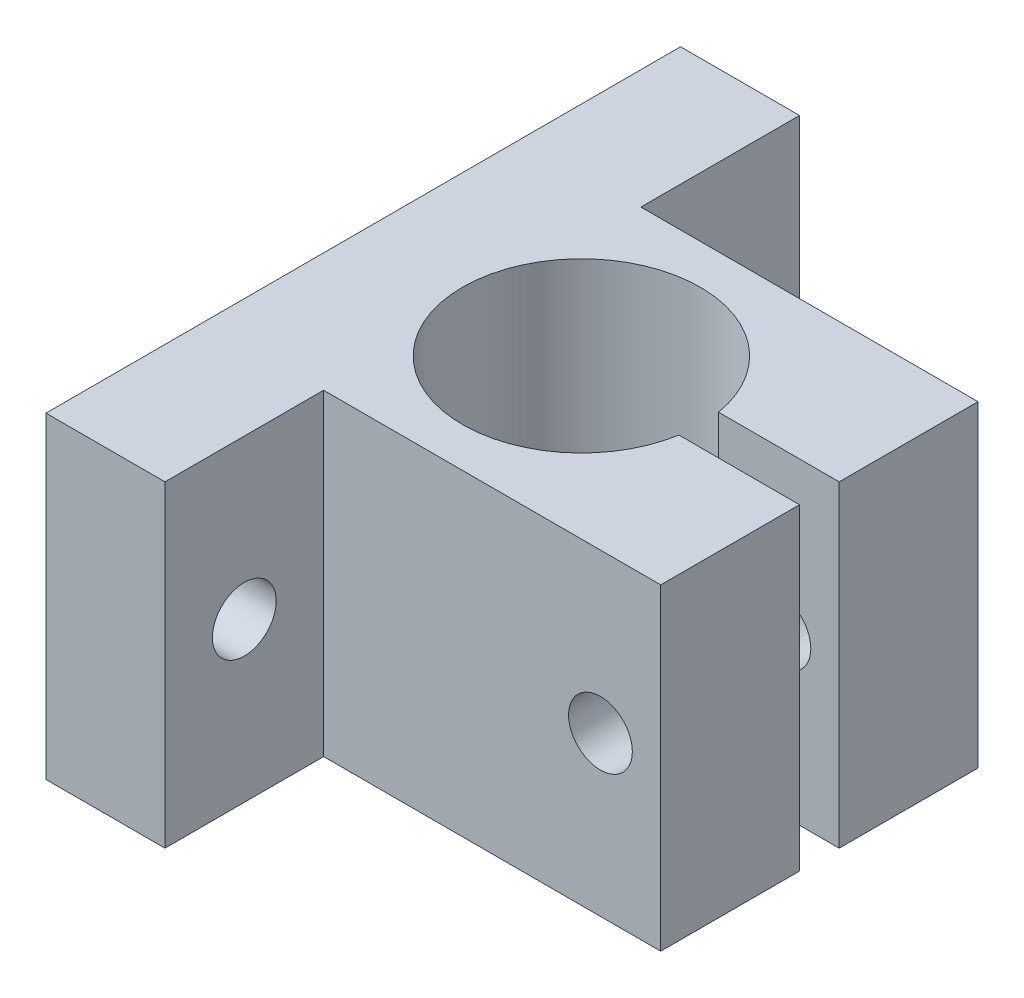
SolidWorks part; units mm, degrees
material "6061 Alloy"
ref_plane "Front Plane" through (0, 0, 0) normal (0, 0, 1) x (1, 0, 0)
ref_plane "Top Plane" through (0, 0, 0) normal (0, 1, 0) x (1, 0, 0)
ref_plane "Right Plane" through (0, 0, 0) normal (1, 0, 0) x (0, 0, -1)
sketch "Sketch1" plane through (0, 0, 0) normal (0, 1, 0) x (1, 0, 0)
  line L1 (-25.4, 25.4) -> (25.4, 25.4)
  line L2 (-25.4, 25.4) -> (-25.4, -25.4)
  line L3 (-25.4, -25.4) -> (25.4, -25.4)
  line L4 (25.4, 25.4) -> (25.4, -25.4)
  line L5 (-25.4, 25.4) -> (25.4, -25.4) construction
  line L6 (-25.4, -25.4) -> (25.4, 25.4) construction
  point P0 (0, 0)
  dimension "D1" = 50.8
  dimension "D2" = 50.8
extrude "Stock block" add sketch "Sketch1" along normal mid plane 25.4
sketch "Sketch2" plane through (0, 12.7, 0) normal (0, 1, 0) x (1, 0, 0)
  line L0 (-25.4, 25.4) -> (-25.4, -25.4) construction
  circle A0 centre (-7.9375, 0) radius 9.525
  dimension "D1" = 19.05
  dimension "D2" = 17.4625
extrude "Sleeve Nut Hole - Large" cut sketch "Sketch2" against normal through all
sketch "Sketch11" plane through (0, 12.7, 0) normal (0, 1, 0) x (1, 0, 0)
  line L0 (25.4, 25.4) -> (-25.4, 25.4) construction
  line L1 (11.1125, 25.4) -> (25.4, 25.4)
  line L2 (11.1125, 25.4) -> (11.1125, -25.4)
  line L3 (11.1125, -25.4) -> (25.4, -25.4)
  line L4 (25.4, 25.4) -> (25.4, -25.4)
  dimension "D1" = 14.2875
extrude "Cut-Extrude4" cut sketch "Sketch11" against normal through all
sketch "Sketch3" plane through (0, 12.7, 0) normal (0, 1, 0) x (1, 0, 0)
  line L0 (-25.4, -25.4) -> (11.1125, -25.4) construction
  line L1 (11.1125, 25.4) -> (-15.875, 25.4)
  line L2 (11.1125, 25.4) -> (11.1125, 12.7)
  line L3 (11.1125, 12.7) -> (-15.875, 12.7)
  line L4 (-15.875, 25.4) -> (-15.875, 12.7)
  line L5 (-15.875, -25.4) -> (11.1125, -25.4)
  line L6 (-15.875, -25.4) -> (-15.875, -12.7)
  line L7 (-15.875, -12.7) -> (11.1125, -12.7)
  line L8 (11.1125, -25.4) -> (11.1125, -12.7)
  line L10 (-25.4, 25.4) -> (-25.4, -25.4) construction
  line L11 (11.1125, 25.4) -> (11.1125, -25.4) construction
  line L12 (11.1125, 25.4) -> (-25.4, 25.4) construction
  dimension "D1" = 9.525
  dimension "D2" = 12.7
extrude "Cut-Extrude2" cut sketch "Sketch3" against normal through all
hole_wizard "#10 Clearance Hole1" positions "Sketch5" profile "Sketch4" hole size "#10" standard "ANSI Inch" end condition up to next
sketch "Sketch5" plane through (-15.875, 0, 0) normal (1, 0, 0) x (0, 0, -1)
  line L22 (-19.05, 12.7) -> (-19.05, -12.7) construction
  line L26 (19.05, 12.7) -> (19.05, -12.7) construction
  line L30 (-25.4, -12.7) -> (-25.4, 12.7) construction
  line L31 (-12.7, 12.7) -> (-25.4, 12.7) construction
  line L32 (-12.7, -12.7) -> (-25.4, -12.7) construction
  line L33 (25.4, -12.7) -> (12.7, -12.7) construction
  line L34 (25.4, 12.7) -> (12.7, 12.7) construction
  line L35 (25.4, -12.7) -> (25.4, 12.7) construction
  point P303 (-19.05, 0)
  point P558 (19.05, 0)
  dimension "D1" = 6.35
  dimension "D2" = 6.35
sketch "Sketch4" plane through (-15.875, 0, 19.05) normal (0, 1, 0) x (0, 0, -1)
  line L0 (0, 0) -> (0, 9.525)
  line L1 (0, 9.525) -> (2.5527, 9.525)
  line L2 (2.5527, 9.525) -> (2.5527, 0)
  line L5 (2.5527, 0) -> (0, 0)
  line L11 (0, -6.35) -> (0, 107.95) construction
  dimension "Thru Hole Dia." = 5.1054
  dimension "Thru Hole Depth" = 9.525
sketch "Sketch6" plane through (11.1125, 0, 0) normal (1, 0, 0) x (0, 0, -1)
  line L1 (0, 18.545) -> (0, -18.545) construction
  line L2 (-1.5875, 18.545) -> (1.5875, 18.545)
  line L3 (-1.5875, 18.545) -> (-1.5875, -18.545)
  line L4 (-1.5875, -18.545) -> (1.5875, -18.545)
  line L6 (1.5875, 18.545) -> (1.5875, -18.545)
  dimension "D1" = 3.175
extrude "Cut-Extrude3" cut sketch "Sketch6" against normal blind 24.13
hole_wizard "#10 Clearance Hole2" positions "Sketch8" profile "Sketch9" hole size "#10" standard "ANSI Inch" end condition through all
sketch "Sketch8" plane through (0, 0, 12.7) normal (0, 0, 1) x (1, 0, 0)
  line L0 (6.2865, 12.7) -> (6.2865, -12.7) construction
  line L1 (11.1125, 12.7) -> (-15.875, 12.7) construction
  line L2 (11.1125, -12.7) -> (-15.875, -12.7) construction
  line L4 (11.1125, -12.7) -> (11.1125, 12.7) construction
  point P13 (6.2865, 0)
  dimension "D3" = 4.826
sketch "Sketch9" plane through (6.2865, 0, 12.7) normal (1, 0, 0) x (0, -1, 0)
  line L0 (0, 0) -> (0, 38.1)
  line L1 (0, 38.1) -> (2.5527, 38.1)
  line L2 (2.5527, 38.1) -> (2.5527, 0)
  line L5 (2.5527, 0) -> (0, 0)
  line L11 (0, -6.35) -> (0, 107.95) construction
  dimension "Thru Hole Dia." = 5.1054
  dimension "Thru Hole Depth" = 38.1
sketch "Sketch10" plane through (-15.875, 0, 0) normal (1, 0, 0) x (0, 0, -1)
  circle A0 centre (19.05, 0) radius 4.7625 construction
  dimension "D1" = 9.525
fillet "Fillet1" [suppressed] radius 3.175
chamfer "Chamfer1" [suppressed] distance 0.508 angle 45
